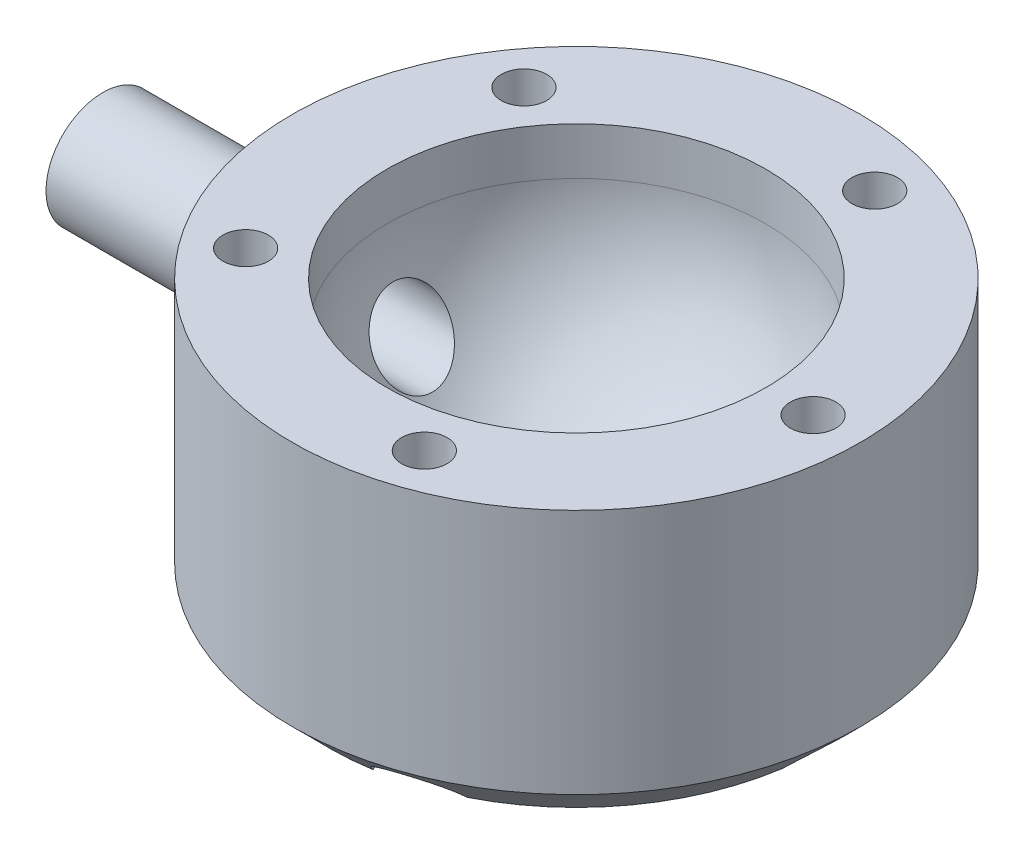
SolidWorks part; units mm, degrees
material "1023 Carbon Steel Sheet (SS)"
ref_plane "Front Plane" through (0, 0, 0) normal (0, 0, 1) x (1, 0, 0)
ref_plane "Top Plane" through (0, 0, 0) normal (0, 1, 0) x (1, 0, 0)
ref_plane "Right Plane" through (0, 0, 0) normal (1, 0, 0) x (0, 0, -1)
sketch "Sketch1" plane through (0, 0, 0) normal (0, 0, 1) x (1, 0, 0)
  line L0 (20, 0) -> (20, -5)
  line L1 (0, 18.5331) -> (0, 32.2934) construction
  line L3 (20, 0) -> (30, 0)
  line L4 (0, -25) -> (0, -30)
  line L5 (55, 0) -> (-55, 0) construction
  line L6 (30, 0) -> (30, -30)
  line L7 (30, -30) -> (0, -30)
  arc A0 (20, -5) -> (0, -25) centre (0, -5) cw
  point P6 (0, 0)
  dimension "D1" = 40
  dimension "D4" = 20
  dimension "D2" = 10
  dimension "D3" = 30
  dimension "D5" = 5
revolve "Revolve1" add sketch "Sketch1" angle 360 about L1
ref_plane "Plane1" through (-50, 0, 0) normal (1, 0, 0) x (0, 0, -1)
sketch "Sketch2" plane through (-50, 0, 0) normal (1, 0, 0) x (0, 0, -1)
  line L0 (38.5, 0) -> (-38.5, 0) construction
  line L1 (0, 6.3515) -> (0, 2.2794) construction
  circle A0 centre (0, -14) radius 6
  dimension "D1" = 12
  dimension "D3" = 14
extrude "Boss-Extrude1" add sketch "Sketch2" along normal up to next
sketch "Sketch4" plane through (-50, 0, 0) normal (-1, 0, 0) x (0, 0, 1)
  circle A0 centre (0, -14) radius 4
  circle A1 centre (0, -14) radius 6 construction
  dimension "D1" = 2
extrude "Cut-Extrude1" cut sketch "Sketch4" against normal up to next
chamfer "Chamfer1" distance 4 angle 45 1 edges at (0, -30, -30)
sketch "Sketch5" plane through (0, 0, 0) normal (0, 1, 0) x (1, 0, 0)
  circle A0 centre (0, 0) radius 25 construction
  circle A1 centre (0, 0) radius 25 construction
  circle A2 centre (0, 0) radius 25 construction
  circle A3 centre (0, 0) radius 25 construction
  circle A4 centre (0, 0) radius 25 construction
  point P3 (25, 0)
  point P7 (7.7254, -23.7764)
  point P9 (-20.2254, -14.6946)
  point P11 (-20.2254, 14.6946)
  point P13 (7.7254, 23.7764)
  point P14 (0, 0)
  dimension "D1" = 50
  dimension "D2" = 5
hole_wizard "CBORE for M4 SHCS1" positions "Sketch6" profile "Sketch7" counterbore size "M4" standard "ANSI Metric" end condition through all
sketch "Sketch6" plane through (0, -30, 0) normal (0, -1, 0) x (-1, 0, 0)
  point P0 (-25, 0)
  point P3 (-7.7254, -23.7764)
  point P6 (20.2254, -14.6946)
  point P9 (20.2254, 14.6946)
  point P12 (-7.7254, 23.7764)
sketch "Sketch7" plane through (25, -30, 0) normal (1, 0, 0) x (0, 0, -1)
  line L0 (0, 0) -> (0, 30)
  line L1 (0, 30) -> (2.4, 30)
  line L3 (2.4, 30) -> (2.4, 19)
  line L4 (2.4, 19) -> (4, 19)
  line L5 (4, 19) -> (4, 0)
  line L7 (4, 0) -> (0, 0)
  line L11 (0, -6.35) -> (0, 107.95) construction
  dimension "Thru Hole Dia." = 4.8
  dimension "Thru Hole Depth" = 30
  dimension "C'Bore Dia." = 8
  dimension "C'Bore Depth" = 19
